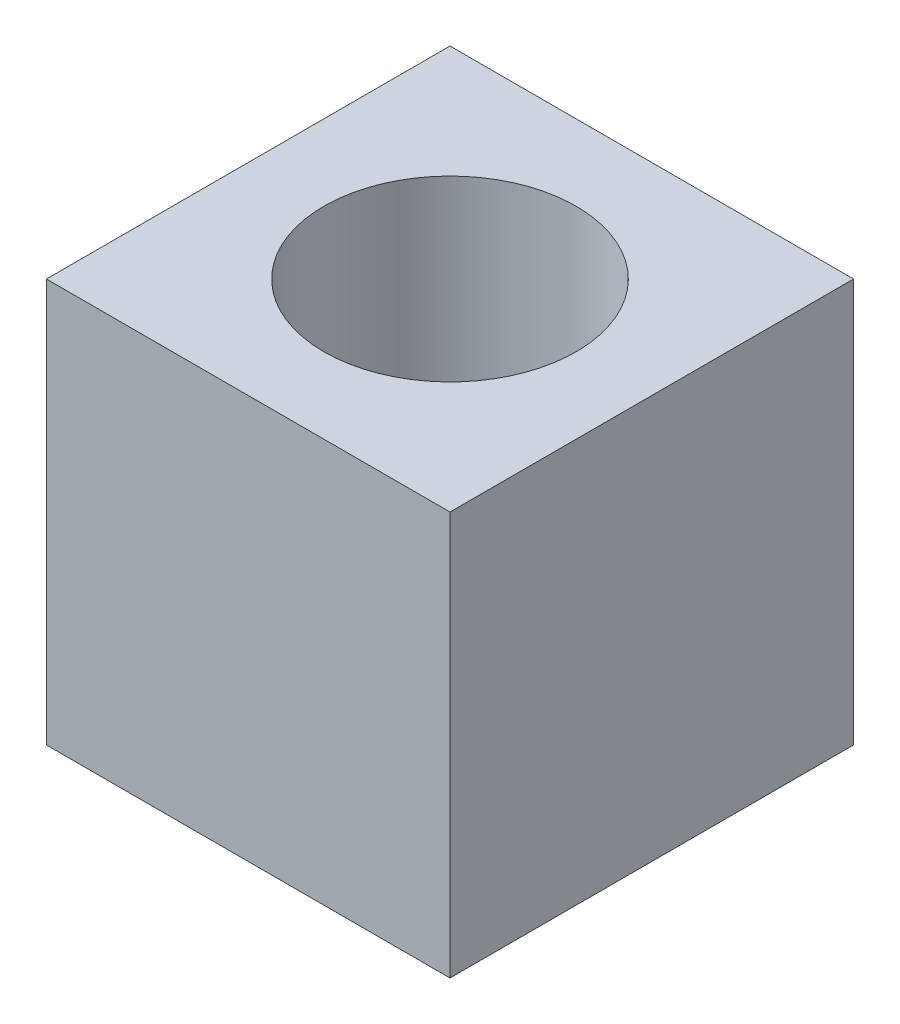
SolidWorks part; units mm, degrees
ref_plane "Front Plane" through (0, 0, 0) normal (0, 0, 1) x (1, 0, 0)
ref_plane "Top Plane" through (0, 0, 0) normal (0, 1, 0) x (1, 0, 0)
ref_plane "Right Plane" through (0, 0, 0) normal (1, 0, 0) x (0, 0, -1)
sketch "Sketch1" plane through (0, 0, 0) normal (0, 0, 1) x (1, 0, 0)
  line L1 (-20, -20) -> (20, -20)
  line L2 (-20, -20) -> (-20, 20)
  line L3 (-20, 20) -> (20, 20)
  line L4 (20, -20) -> (20, 20)
  line L5 (-20, -20) -> (20, 20) construction
  line L6 (-20, 20) -> (20, -20) construction
  point P0 (0, 0)
  dimension "D1" = 40
extrude "Boss-Extrude1" add sketch "Sketch1" along normal mid plane 40
sketch "Sketch2" plane through (0, 0, 0) normal (0, 1, 0) x (0, 0, 1)
  circle A0 centre (0, 0) radius 12.5
  dimension "D1" = 25
extrude "Cut-Extrude2" cut sketch "Sketch2" against normal through all both and the other way through all contours A0
